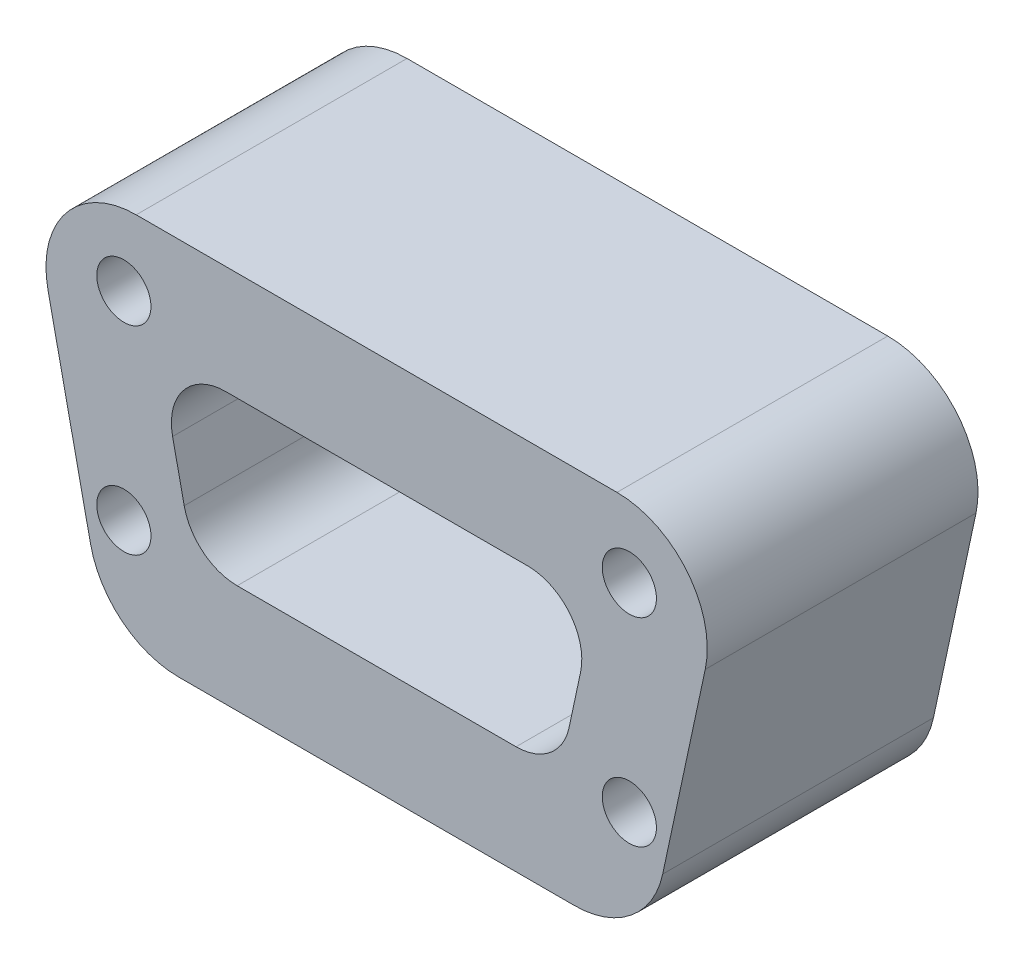
SolidWorks part; units mm, degrees
material "PLA"
ref_plane "前视基准面" through (0, 0, 0) normal (0, 0, 1) x (1, 0, 0)
ref_plane "上视基准面" through (0, 0, 0) normal (0, 1, 0) x (1, 0, 0)
ref_plane "右视基准面" through (0, 0, 0) normal (1, 0, 0) x (0, 0, -1)
sketch "草图1" plane through (0, 0, 0) normal (0, 0, 1) x (1, 0, 0)
  line L0 (19.5, 9.5) -> (-19.5, 9.5)
  line L1 (-14, 5.5) -> (14, 5.5) construction
  line L2 (-14, 5.5) -> (-14, -5.5) construction
  line L3 (-14, -5.5) -> (14, -5.5) construction
  line L4 (14, 5.5) -> (14, -5.5) construction
  line L5 (-14, 5.5) -> (14, -5.5) construction
  line L6 (-14, -5.5) -> (14, 5.5) construction
  line L7 (15, -11.5) -> (-15, -11.5)
  line L8 (19.5, 9.5) -> (15, -11.5)
  line L9 (-19.5, 9.5) -> (-15, -11.5)
  line L10 (-12.0781, 3.5) -> (-10.1495, -5.5)
  line L11 (10.1495, -5.5) -> (-10.1495, -5.5)
  line L12 (12.0781, 3.5) -> (10.1495, -5.5)
  line L13 (12.0781, 3.5) -> (-12.0781, 3.5)
  circle A0 centre (14, -5.5) radius 1.5
  circle A1 centre (-14, -5.5) radius 1.5
  circle A2 centre (-14, 5.5) radius 1.5
  circle A3 centre (14, 5.5) radius 1.5
  point P0 (0, 0)
  point P8 (0, 9.5)
  point P11 (0, -11.5)
  dimension "D6" = 3
  dimension "D7" = 3
  dimension "D8" = 3
  dimension "D9" = 3
  dimension "D1" = 11
  dimension "D2" = 28
  dimension "D3" = 39
  dimension "D4" = 30
  dimension "D5" = 11.5
  dimension "D10" = 21
  dimension "D11" = 6
extrude "凸台-拉伸1" add sketch "草图1" along normal blind 15
fillet "圆角1" radius 5 4 edges at (-15, -11.5, 7.5) (15, -11.5, 7.5) (-19.5, 9.5, 7.5) (19.5, 9.5, 7.5)
fillet "圆角2" radius 3 4 edges at (-10.1495, -5.5, 7.5) (10.1495, -5.5, 7.5) (12.0781, 3.5, 7.5) (-12.0781, 3.5, 7.5)
